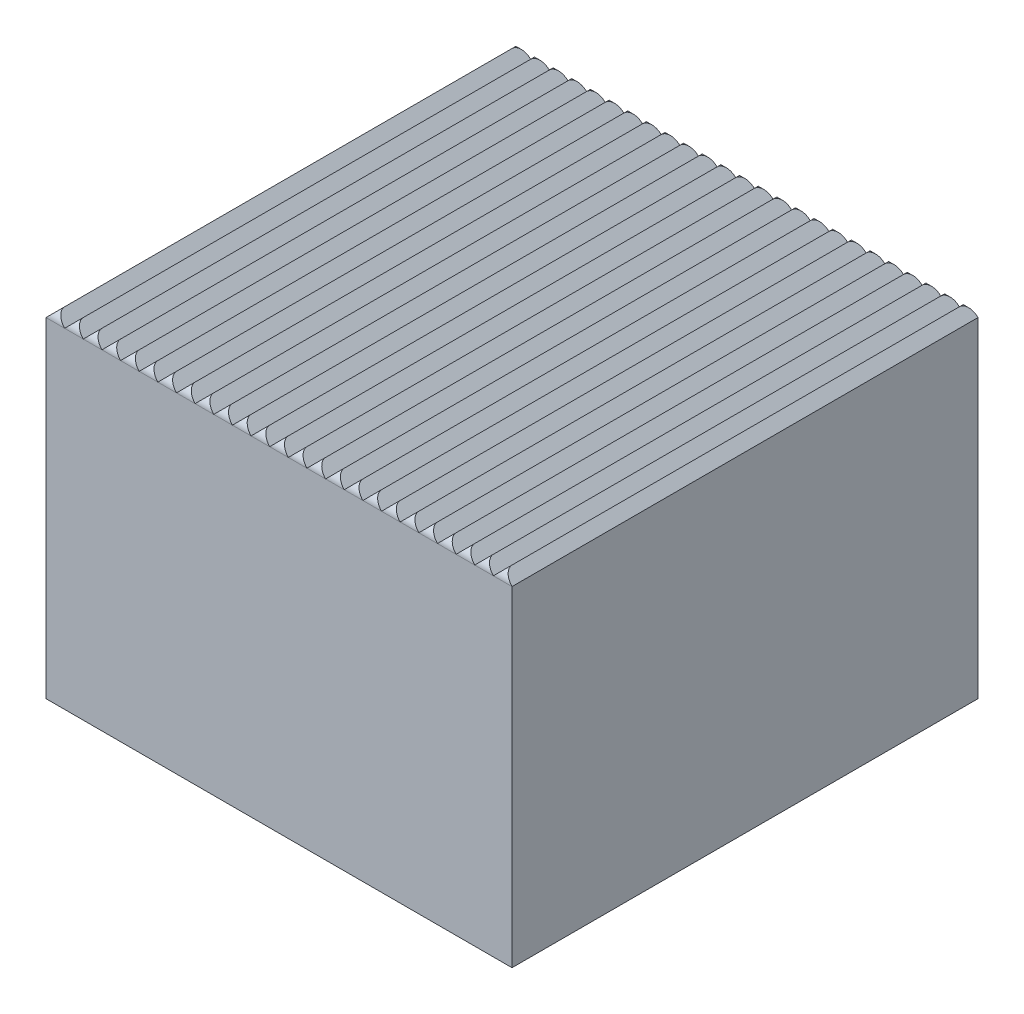
SolidWorks part; units mm, degrees
ref_plane "Front Plane" through (0, 0, 0) normal (0, 0, 1) x (1, 0, 0)
ref_plane "Top Plane" through (0, 0, 0) normal (0, 1, 0) x (1, 0, 0)
ref_plane "Right Plane" through (0, 0, 0) normal (1, 0, 0) x (0, 0, -1)
sketch "Sketch1" plane through (0, 0, 0) normal (0, 1, 0) x (1, 0, 0)
  line L0 (-27.5, 27.5) -> (27.5, 27.5)
  line L1 (-30, -30) -> (30, -30)
  line L2 (-30, -30) -> (-30, 30)
  line L3 (-30, 30) -> (30, 30)
  line L4 (30, -30) -> (30, 30)
  line L5 (-30, -30) -> (30, 30) construction
  line L6 (-30, 30) -> (30, -30) construction
  line L7 (27.5, -27.5) -> (27.5, 27.5)
  line L8 (-27.5, -27.5) -> (27.5, -27.5)
  line L9 (-27.5, -27.5) -> (-27.5, 27.5)
  point P0 (0, 0)
  dimension "D1" = 60
  dimension "D2" = 60
  dimension "D3" = 2.5
extrude "Boss-Extrude1" add sketch "Sketch1" along normal blind 40
sketch "Sketch2" plane through (0, 40, 0) normal (0, 1, 0) x (1, 0, 0)
  line L1 (-30, 30) -> (30, 30)
  line L2 (-30, 30) -> (-30, -30)
  line L3 (-30, -30) -> (30, -30)
  line L4 (30, 30) -> (30, -30)
extrude "Boss-Extrude2" add sketch "Sketch2" along normal blind 2.5
sketch "Sketch3" plane through (0, 0, -30) normal (0, 0, -1) x (-1, 0, 0)
  line L0 (-30, 42.5) -> (-28.8, 43.7)
  line L1 (-28.8, 43.7) -> (-27.6, 42.5)
  line L2 (-30, 42.5) -> (30, 42.5) construction
  line L3 (-27.6, 42.5) -> (-26.4, 43.7)
  line L4 (-26.4, 43.7) -> (-25.2, 42.5)
  line L5 (-25.2, 42.5) -> (-24, 43.7)
  line L6 (-24, 43.7) -> (-22.8, 42.5)
  line L7 (-22.8, 42.5) -> (-21.6, 43.7)
  line L8 (-21.6, 43.7) -> (-20.4, 42.5)
  line L9 (-20.4, 42.5) -> (-19.2, 43.7)
  line L10 (-19.2, 43.7) -> (-18, 42.5)
  line L11 (-18, 42.5) -> (-16.8, 43.7)
  line L12 (-16.8, 43.7) -> (-15.6, 42.5)
  line L13 (-15.6, 42.5) -> (-14.4, 43.7)
  line L14 (-14.4, 43.7) -> (-13.2, 42.5)
  line L15 (-13.2, 42.5) -> (-12, 43.7)
  line L16 (-12, 43.7) -> (-10.8, 42.5)
  line L17 (-10.8, 42.5) -> (-9.6, 43.7)
  line L18 (-9.6, 43.7) -> (-8.4, 42.5)
  line L19 (-8.4, 42.5) -> (-7.2, 43.7)
  line L20 (-7.2, 43.7) -> (-6, 42.5)
  line L21 (-6, 42.5) -> (-4.8, 43.7)
  line L22 (-4.8, 43.7) -> (-3.6, 42.5)
  line L23 (-3.6, 42.5) -> (-2.4, 43.7)
  line L24 (-2.4, 43.7) -> (-1.2, 42.5)
  line L25 (-1.2, 42.5) -> (0, 43.7)
  line L26 (0, 43.7) -> (1.2, 42.5)
  line L27 (1.2, 42.5) -> (2.4, 43.7)
  line L28 (2.4, 43.7) -> (3.6, 42.5)
  line L29 (3.6, 42.5) -> (4.8, 43.7)
  line L30 (4.8, 43.7) -> (6, 42.5)
  line L31 (6, 42.5) -> (7.2, 43.7)
  line L32 (7.2, 43.7) -> (8.4, 42.5)
  line L33 (8.4, 42.5) -> (9.6, 43.7)
  line L34 (9.6, 43.7) -> (10.8, 42.5)
  line L35 (10.8, 42.5) -> (12, 43.7)
  line L36 (12, 43.7) -> (13.2, 42.5)
  line L37 (13.2, 42.5) -> (14.4, 43.7)
  line L38 (14.4, 43.7) -> (15.6, 42.5)
  line L39 (15.6, 42.5) -> (16.8, 43.7)
  line L40 (16.8, 43.7) -> (18, 42.5)
  line L41 (18, 42.5) -> (19.2, 43.7)
  line L42 (19.2, 43.7) -> (20.4, 42.5)
  line L43 (20.4, 42.5) -> (21.6, 43.7)
  line L44 (21.6, 43.7) -> (22.8, 42.5)
  line L45 (22.8, 42.5) -> (24, 43.7)
  line L46 (24, 43.7) -> (25.2, 42.5)
  line L47 (25.2, 42.5) -> (26.4, 43.7)
  line L48 (26.4, 43.7) -> (27.6, 42.5)
  line L49 (27.6, 42.5) -> (28.8, 43.7)
  line L50 (28.8, 43.7) -> (30, 42.5)
  line L51 (-30, 42.5) -> (-30, 42.1701)
  line L52 (-30, 42.5) -> (-30, 0) construction
  line L53 (-30, 42.1701) -> (30, 42.1701)
  line L54 (30, 42.5) -> (30, 0) construction
  line L55 (30, 42.1701) -> (30, 42.5)
  dimension "D1" = 2.4
  dimension "D2" = 1.6971
  dimension "D3" = 25
extrude "Boss-Extrude3" add sketch "Sketch3" against normal up to surface (60 mm away) contours L46 L47 L48 L49 L50 L55 L53 L51 L0 L1 L3 L4 L5 L6 L7 L8 L9 L10 L11 L12 L13 L14 L15 L16 L17 L18 L19 L20 L21 L22 L23 L24 L25 L26 L27 L28 L29 L30 L31 L32 L33 L34 L35 L36 L37 L38 L39 L40 L41 L42 L43 L44 L45 up to face at (0, 21.25, 30)
sketch "Sketch4" plane through (-30, 0, 0) normal (-1, 0, 0) x (0, 0, 1)
  line L0 (-28.8, 42.5) -> (-28.8, 43.7) construction
  line L1 (-28.8, 43.7) -> (-28.8, 42.5) construction
  line L2 (-28.8, 42.5) -> (-30, 42.5) construction
  line L3 (-30, 42.5) -> (-30, 0) construction
  line L4 (30, 43.7) -> (-30, 43.7) construction
  line L5 (-30, 42.5) -> (-30, 43.7)
  line L6 (-30, 43.7) -> (-28.8, 43.7)
  arc A0 (-28.8, 43.7) -> (-30, 42.5) centre (-28.8, 42.5) ccw
  dimension "D1" = 1.2
extrude "Cut-Extrude1" cut sketch "Sketch4" against normal up to surface (60 mm away) up to face at (30, 21.25, 0)
mirror "Mirror1" about plane through (0, 0, 0) normal (0, 0, 1) of "Cut-Extrude1"
